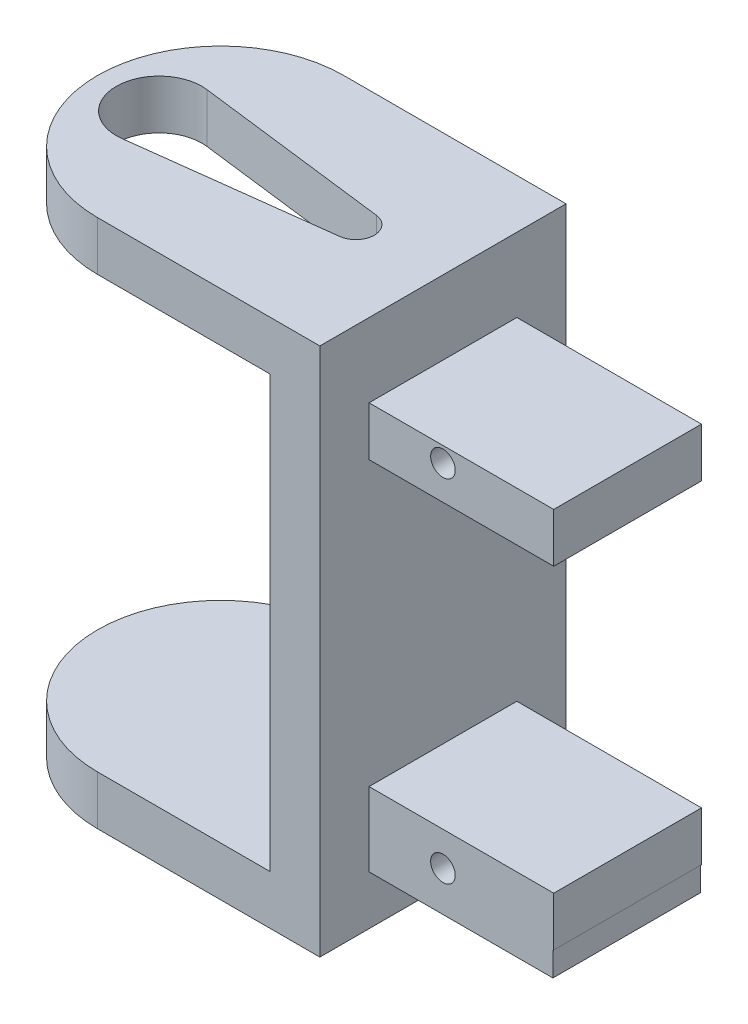
SolidWorks part; units mm, degrees
ref_plane "前视基准面" through (0, 0, 0) normal (0, 0, 1) x (1, 0, 0)
ref_plane "上视基准面" through (0, 0, 0) normal (0, 1, 0) x (1, 0, 0)
ref_plane "右视基准面" through (0, 0, 0) normal (1, 0, 0) x (0, 0, -1)
sketch "草图1" plane through (0, 0, 0) normal (0, 0, 1) x (1, 0, 0)
  line L0 (25.0621, 0) -> (25.0621, -46)
  line L1 (0, 0) -> (25.0621, 0)
  line L2 (0, 0) -> (0, -46)
  line L3 (0, -46) -> (25.0621, -46)
  line L5 (0, -4) -> (20, -4)
  line L6 (0, -4) -> (0, -42)
  line L7 (0, -42) -> (20, -42)
  line L8 (20, -4) -> (20, -42)
  dimension "D1" = 38
  dimension "D3" = 4
  dimension "D4" = 4
  dimension "D5" = 20
extrude "凸台-拉伸1" add sketch "草图1" along normal blind 20 contours L5 L8 L7 L2 L3 L0 L1
sketch "草图3" plane through (0, 0, 0) normal (0, 1, 0) x (1, 0, 0)
  line L0 (0, 0) -> (0, -20)
  line L1 (0, -20) -> (0, -10)
  line L4 (5.4293, -6.5516) -> (21.1703, -8.5115)
  line L5 (5.4293, -13.4484) -> (21.1703, -11.4885)
  arc A1 (5.4293, -6.5516) -> (5.4293, -13.4484) centre (5, -10) ccw
  arc A2 (21.1703, -11.4885) -> (21.1703, -8.5115) centre (20.985, -10) ccw
  dimension "D2" = 6.95
  dimension "D4" = 3
  dimension "D1" = 5
extrude "切除-拉伸2" cut sketch "草图3" against normal blind 20 contours L5 A2 L4 A1
sketch "草图6" plane through (25.0621, 0, 0) normal (1, 0, 0) x (0, 0, -1)
  line L1 (-20, 0) -> (0, 0)
  line L2 (-20, 0) -> (-20, -46)
  line L3 (-20, -46) -> (0, -46)
  line L4 (0, 0) -> (0, -46)
extrude "凸台-拉伸2" add sketch "草图6" along normal blind 3
sketch "草图7" plane through (0, 0, 20) normal (0, 0, 1) x (1, 0, 0)
  line L0 (20, -4) -> (20, -42)
  line L1 (20, -4) -> (24, -4)
  line L2 (20, -42) -> (24, -42)
  line L3 (24, -4) -> (24, -42)
  dimension "D1" = 4
extrude "切除-拉伸4" cut sketch "草图7" against normal blind 23
sketch "草图8" plane through (0, -42, 0) normal (0, 1, 0) x (1, 0, 0)
  line L0 (0, 0) -> (0, -20)
  line L1 (0, 0) -> (27.0474, 0)
  line L2 (0, -20) -> (27.0474, -20)
  line L3 (27.0474, 0) -> (27.0474, -20)
extrude "凸台-拉伸3" add sketch "草图8" along normal blind 3
sketch "草图9" plane through (0, 0, 20) normal (0, 0, 1) x (1, 0, 0)
  line L0 (0, -46) -> (28.0621, -46)
  line L1 (0, -46) -> (0, -43)
  line L2 (28.0621, -46) -> (28.0621, -43)
  line L3 (0, -43) -> (28.0621, -43)
  dimension "D1" = 3
extrude "切除-拉伸5" cut sketch "草图9" against normal blind 50 contours L0 L1 L3 L2
sketch "草图10" plane through (0, 0, 0) normal (0, 1, 0) x (1, 0, 0)
  line L0 (0, 0) -> (28.0621, 0)
  line L1 (0, 0) -> (0, -10)
  line L2 (10, -20) -> (28.0621, -20)
  line L3 (0, 0) -> (0, -20)
  line L4 (0, -20) -> (0, -10)
  line L5 (0, -10) -> (-3.7027, -10)
  arc A0 (10, 0) -> (10, -20) centre (10, -10) ccw
  point P10 (0, -20)
  line M9 (0, 0) -> (0, -20)
  line M10 (0, -20) -> (28.0621, -20)
  dimension "D1" = 10
extrude "切除-拉伸6" cut sketch "草图10" against normal blind 50 contours A0 L0 M9 | A0 M9 M10
sketch "草图11" plane through (28.0621, 0, 0) normal (1, 0, 0) x (0, 0, -1)
  line L0 (-20, 0) -> (0, 0)
  line L1 (0, 0) -> (-10, 0)
  line L2 (-10, 0) -> (-10, -43)
  line L3 (-20, -43) -> (0, -43) construction
  line L4 (-16.0017, -10) -> (-3.9983, -10)
  line L5 (-16.0017, -10) -> (-3.9983, -10)
  line L6 (-16.0017, -10) -> (-16.0017, -33)
  line L7 (-16.0017, -33) -> (-3.9983, -33)
  line L8 (-3.9983, -10) -> (-3.9983, -33)
  line L9 (-16.0017, -10) -> (-3.9983, -33) construction
  line L10 (-16.0017, -33) -> (-3.9983, -10) construction
  line L11 (-16.0017, -10) -> (-16.0017, -6)
  line L12 (-3.9983, -10) -> (-3.9983, -6)
  line L13 (-16.0017, -6) -> (-3.9983, -6)
  line L14 (-16.0017, -33) -> (-3.9983, -33)
  line L15 (-16.0017, -33) -> (-16.0017, -37)
  line L16 (-3.9983, -33) -> (-3.9983, -37)
  line L17 (-16.0017, -37) -> (-3.9983, -37)
  point P4 (-10, -21.5)
  dimension "D1" = 23
  dimension "D2" = 4
  dimension "D3" = 4
extrude "凸台-拉伸4" add sketch "草图11" along normal blind 15 contours L13 L11 L4 L2 | L13 L2 L4 L12 | L2 L17 L16 L7 | L15 L17 L2 L7
sketch "草图16" plane through (0, -37, 0) normal (0, -1, 0) x (1, 0, 0)
  line L0 (28.0621, 16.0017) -> (28.0621, 3.9983)
  line L1 (28.0621, 16.0017) -> (42.9967, 16.0017)
  line L2 (28.0621, 3.9983) -> (42.9967, 3.9983)
  line L3 (42.9967, 16.0017) -> (42.9967, 3.9983)
extrude "凸台-拉伸5" add sketch "草图16" along normal blind 2
sketch "草图18" plane through (0, -39, 0) normal (0, -1, 0) x (1, 0, 0)
  line L0 (28.0621, 16.0017) -> (28.0621, 3.9983)
  line L1 (28.0621, 16.0017) -> (43.0978, 16.0017)
  line L2 (28.0621, 3.9983) -> (43.0978, 3.9983)
  line L3 (43.0978, 16.0017) -> (43.0978, 3.9983)
sketch "草图19" plane through (43.0621, 0, 0) normal (1, 0, 0) x (0, 0, -1)
  line L0 (-16.0017, -10) -> (-3.9983, -10)
  line L1 (-3.9983, -10) -> (-10, -10)
  line L2 (-10, -10) -> (-10, -7.25)
  line L3 (-10, -7.25) -> (-10, -35.75)
  circle A0 centre (-10, -7.25) radius 1
  circle A1 centre (-10, -35.75) radius 1
  dimension "D2" = 2
  dimension "D4" = 2
  dimension "D1" = 2.75
  dimension "D3" = 28.5
sketch "草图21" plane through (0, 0, 16.0017) normal (0, 0, 1) x (1, 0, 0)
  line L0 (28.0621, -10) -> (34.0621, -10)
  line L1 (43.0621, -10) -> (28.0621, -10) construction
  line L3 (28.0621, -10) -> (34.0621, -10)
  line L4 (28.0621, -33) -> (35.0175, -33)
  line L6 (34.0621, -10) -> (34.0621, -7.25)
  line L7 (34.0621, -7.25) -> (34.0621, -35.75)
  circle A0 centre (34.0621, -7.25) radius 1
  circle A1 centre (34.0621, -35.75) radius 1
  dimension "D4" = 2
  dimension "D6" = 2
  dimension "D1" = 6
  dimension "D2" = 6
  dimension "D3" = 2.75
  dimension "D5" = 28.5
extrude "切除-拉伸8" cut sketch "草图21" against normal blind 10
